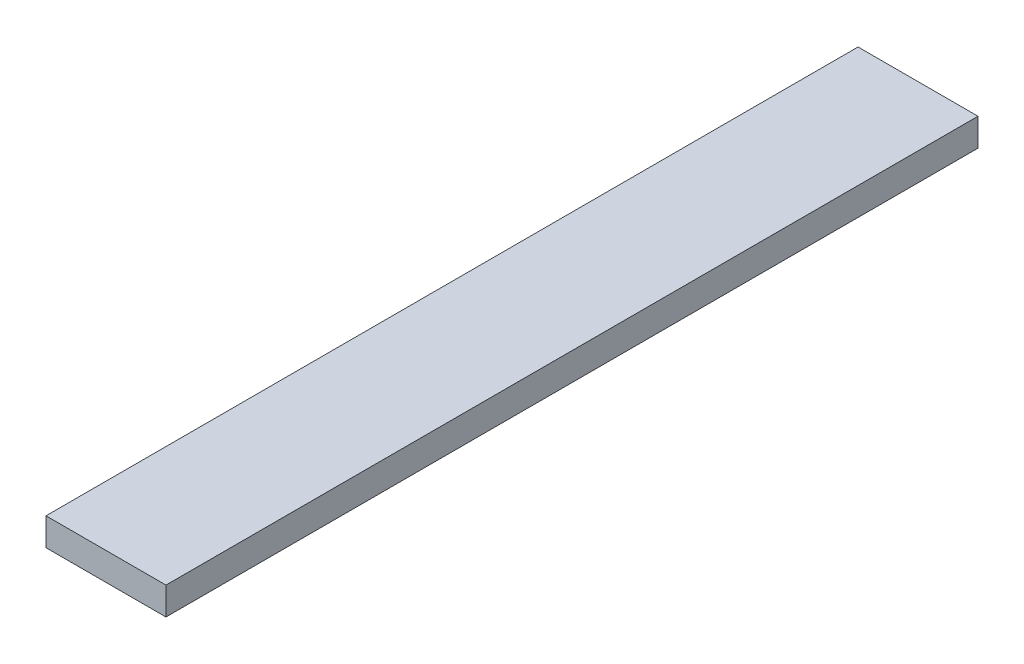
SolidWorks part; units mm, degrees
ref_plane "Front Plane" through (0, 0, 0) normal (0, 0, 1) x (1, 0, 0)
ref_plane "Top Plane" through (0, 0, 0) normal (0, 1, 0) x (1, 0, 0)
ref_plane "Right Plane" through (0, 0, 0) normal (1, 0, 0) x (0, 0, -1)
sketch "Sketch1" plane through (0, 0, 0) normal (0, 0, 1) x (1, 0, 0)
  line L1 (0, 0) -> (41.275, 0)
  line L2 (0, 0) -> (0, 9.525)
  line L3 (0, 9.525) -> (41.275, 9.525)
  line L4 (41.275, 0) -> (41.275, 9.525)
  dimension "D1" = 9.525
  dimension "D2" = 41.275
extrude "Boss-Extrude1" add sketch "Sketch1" along normal blind 279.4
